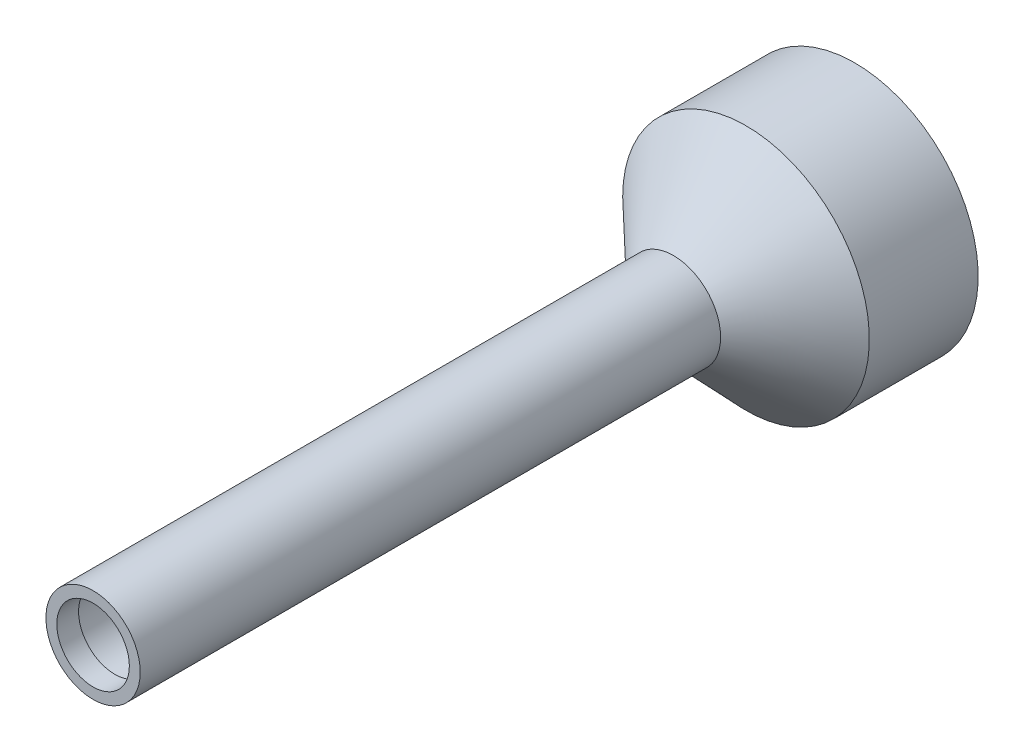
SolidWorks part; units mm, degrees
ref_plane "Front Plane" through (0, 0, 0) normal (0, 0, 1) x (1, 0, 0)
ref_plane "Top Plane" through (0, 0, 0) normal (0, 1, 0) x (1, 0, 0)
ref_plane "Right Plane" through (0, 0, 0) normal (1, 0, 0) x (0, 0, -1)
sketch "Sketch1" plane through (0, 0, 0) normal (0, 0, 1) x (1, 0, 0)
  circle A0 centre (0, 0) radius 15.65
  circle A1 centre (0, 0) radius 17
  dimension "D1" = 31.3
  dimension "D2" = 34
ref_plane "Plane1" through (0, 0, 10) normal (0, 0, 1) x (1, 0, 0)
sketch "Sketch2" plane through (0, 0, 10) normal (0, 0, 1) x (1, 0, 0)
  circle A0 centre (0, 0) radius 5
  circle A1 centre (0, 0) radius 6.5
  dimension "D1" = 10
  dimension "D2" = 13
loft "Loft1" add section "Sketch1" section "Sketch2"
sketch "Sketch3" plane through (0, 0, 10) normal (0, 0, 1) x (1, 0, 0)
  circle A0 centre (0, 0) radius 5 construction
  circle A1 centre (0, 0) radius 6.5
  circle A2 centre (0, 0) radius 6.5
  circle A3 centre (0, 0) radius 5
  dimension "D1" = 0
extrude "Boss-Extrude1" add sketch "Sketch3" along normal blind 80
shell "Shell1" thickness 3
sketch "Sketch4" plane through (0, 0, 7) normal (0, 0, -1) x (-1, 0, 0)
  circle A1 centre (0, 0) radius 5.3
  circle A2 centre (0, 0) radius 5.3
  dimension "D1" = 0
extrude "Cut-Extrude1" cut sketch "Sketch4" against normal blind 80
sketch "Sketch5" plane through (0, 0, 0) normal (0, 0, -1) x (-1, 0, 0)
  circle A0 centre (0, 0) radius 12.65 construction
  circle A1 centre (0, 0) radius 17
  circle A2 centre (0, 0) radius 17
  circle A3 centre (0, 0) radius 12.65
  dimension "D1" = 0
extrude "Boss-Extrude2" add sketch "Sketch5" along normal blind 15
